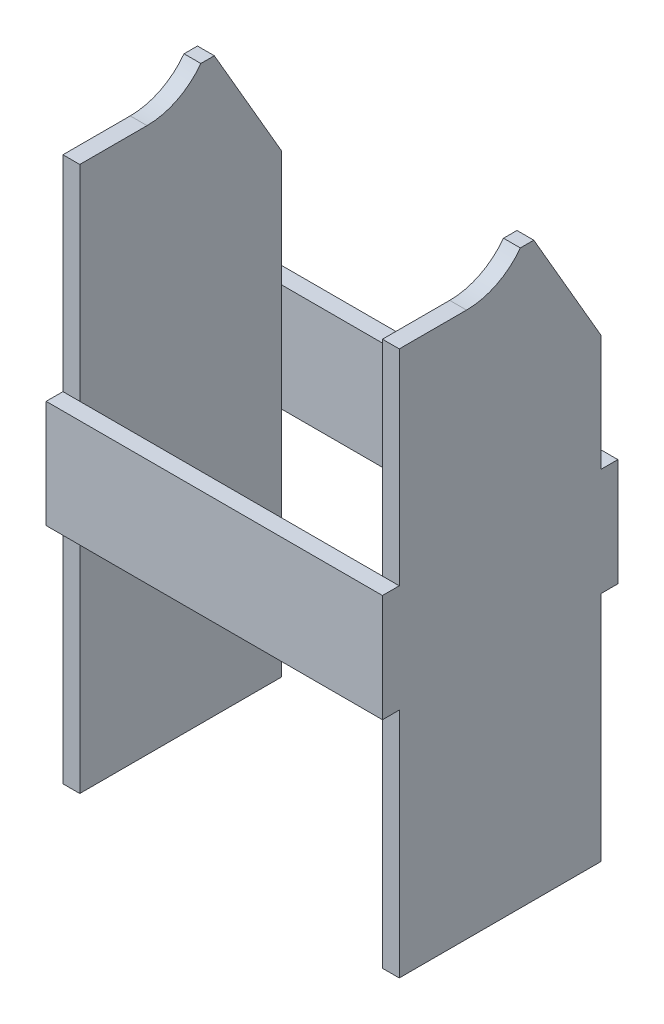
SolidWorks part; units mm, degrees
ref_plane "前视基准面" through (0, 0, 0) normal (0, 0, 1) x (1, 0, 0)
ref_plane "上视基准面" through (0, 0, 0) normal (0, 1, 0) x (1, 0, 0)
ref_plane "右视基准面" through (0, 0, 0) normal (1, 0, 0) x (0, 0, -1)
sketch "草图1" plane through (0, 0, 0) normal (0, 1, 0) x (1, 0, 0)
  line L0 (-64.9635, 0) -> (0, 0) construction
  line L1 (0, 0) -> (0, 72.8102) construction
  line L3 (-50, 30) -> (-45, 30)
  line L4 (-50, 30) -> (-50, -30)
  line L5 (-50, -30) -> (-45, -30)
  line L6 (-45, 30) -> (-45, -30)
  line L7 (45, 30) -> (50, 30)
  line L8 (45, 30) -> (45, -30)
  line L9 (45, -30) -> (50, -30)
  line L10 (50, 30) -> (50, -30)
  dimension "D1" = 45
  dimension "D2" = 45
  dimension "D3" = 60
  dimension "D4" = 30
  dimension "D5" = 60
  dimension "D6" = 30
  dimension "D7" = 5
  dimension "D8" = 5
extrude "凸台-拉伸1" add sketch "草图1" along normal blind 170
sketch "草图2" plane through (50, 0, 0) normal (1, 0, 0) x (0, 0, -1)
  line L0 (0, 0) -> (0, 170) construction
  line L1 (-30, 170) -> (30, 170) construction
  line L2 (-30, 85) -> (30, 85) construction
  line L3 (-30, 170) -> (-30, 0) construction
  line L4 (30, 170) -> (30, 0) construction
  line L6 (-30, 101) -> (-35, 101)
  line L7 (-30, 101) -> (-30, 69)
  line L8 (-30, 69) -> (-35, 69)
  line L9 (-35, 101) -> (-35, 69)
  line L10 (30, 101) -> (35, 101)
  line L11 (30, 101) -> (30, 69)
  line L12 (30, 69) -> (35, 69)
  line L13 (35, 101) -> (35, 69)
  dimension "D1" = 5
  dimension "D2" = 32
  dimension "D3" = 16
  dimension "D4" = 5
  dimension "D5" = 32
  dimension "D6" = 16
extrude "凸台-拉伸2" add sketch "草图2" against normal blind 100
sketch "草图3" plane through (-50, 0, 0) normal (-1, 0, 0) x (0, 0, 1)
  line L0 (-10, 170) -> (-30, 135.5)
  line L2 (-30, 170) -> (30, 170) construction
  line L3 (10, 162) -> (30, 162)
  line L4 (30, 170) -> (30, 101) construction
  line L5 (30, 162) -> (30, 182)
  line L6 (-30, 170) -> (-30, 101) construction
  line L7 (-30, 135.5) -> (-48.5689, 135.5)
  line L8 (-48.5689, 135.5) -> (-48.5689, 174.5911)
  line L9 (-48.5689, 174.5911) -> (-10, 174.5911)
  line L10 (-10, 174.5911) -> (-10, 170)
  arc A0 (30, 182) -> (10, 162) centre (10, 182) ccw
  dimension "D1" = 12
  dimension "D2" = 20
extrude "切除-拉伸2" cut sketch "草图3" against normal blind 120
